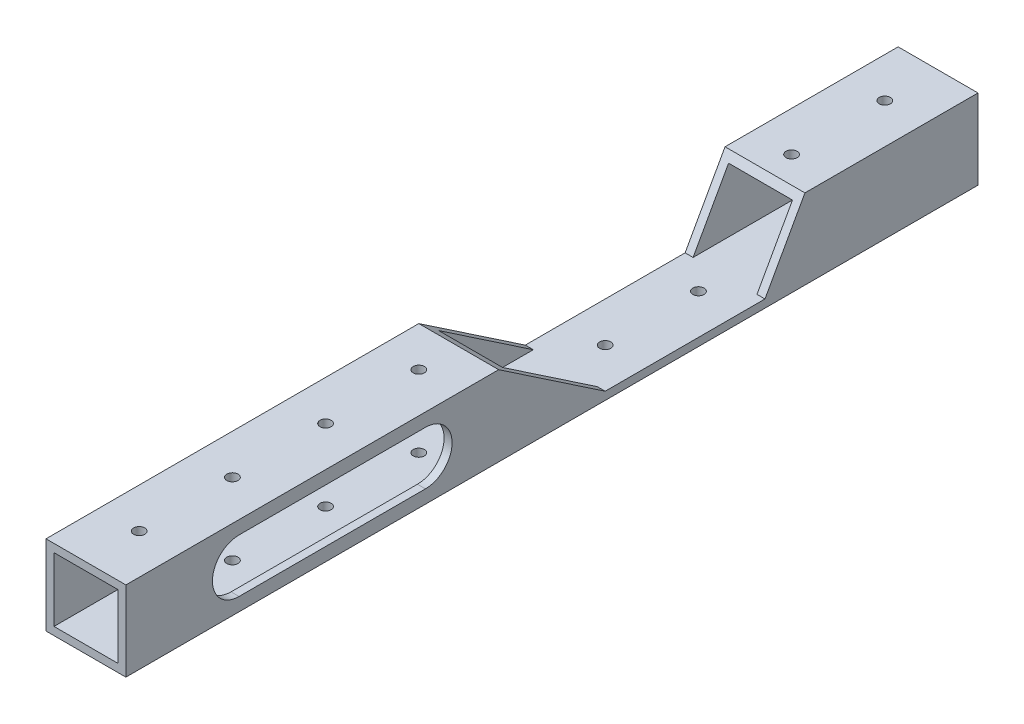
SolidWorks part; units mm, degrees
material "6061 合金"
ref_plane "前视基准面" through (0, 0, 0) normal (0, 0, 1) x (1, 0, 0)
ref_plane "上视基准面" through (0, 0, 0) normal (0, 1, 0) x (1, 0, 0)
ref_plane "右视基准面" through (0, 0, 0) normal (1, 0, 0) x (0, 0, -1)
sketch "草图1" plane through (0, 0, 0) normal (0, 0, 1) x (1, 0, 0)
  line L1 (0, 0) -> (30, 0)
  line L2 (0, 0) -> (0, 30)
  line L3 (0, 30) -> (30, 30)
  line L4 (30, 0) -> (30, 30)
  dimension "D1" = 30
  dimension "D2" = 30
extrude "拉伸-薄壁1" add sketch "草图1" along normal blind 320 thin thin type one direction reverse wall 3
sketch "草图2" plane through (30, 0, 0) normal (1, 0, 0) x (0, 0, -1)
  line L0 (-160, 30) -> (-160, 0) construction
  line L1 (-320, 30) -> (0, 30) construction
  line L2 (-320, 0) -> (0, 0) construction
  line L3 (-320, 15) -> (0, 15) construction
  line L4 (-320, 0) -> (-320, 30) construction
  line L5 (0, 0) -> (0, 30) construction
  line L6 (-242.5, 0) -> (-242.5, 30) construction
  line L7 (-277.5, 15) -> (-207.5, 15) construction
  line L8 (-277.5, 25) -> (-207.5, 25)
  line L9 (-277.5, 5) -> (-207.5, 5)
  arc A1 (-277.5, 25) -> (-277.5, 5) centre (-277.5, 15) ccw
  arc A2 (-207.5, 5) -> (-207.5, 25) centre (-207.5, 15) ccw
  point P14 (-242.5, 15)
  point P17 (-242.5, 15)
  point P20 (-242.5, 15)
  dimension "D1" = 82.5
  dimension "D2" = 30
  dimension "D3" = 20
  dimension "D4" = 70
extrude "切除-拉伸1" cut sketch "草图2" against normal through all
sketch "草图3" plane through (0, 30, 0) normal (0, 1, 0) x (1, 0, 0)
  line L0 (0, -160) -> (30, -160) construction
  line L1 (0, -320) -> (0, 0) construction
  line L2 (30, -320) -> (30, 0) construction
  line L3 (15, 0) -> (15, -320) construction
  line L4 (30, 0) -> (0, 0) construction
  line L5 (30, -320) -> (0, -320) construction
  circle A0 centre (15, -20) radius 2.1
  circle A1 centre (15, -55) radius 2.1
  circle A2 centre (15, -90) radius 2.1
  circle A3 centre (15, -125) radius 2.1
  circle A4 centre (15, -300) radius 2.1
  circle A5 centre (15, -265) radius 2.1
  circle A6 centre (15, -230) radius 2.1
  circle A7 centre (15, -195) radius 2.1
  circle A8 centre (15, -160) radius 2.1
  dimension "D1" = 20
  dimension "D2" = 35
  dimension "D3" = 35
  dimension "D4" = 35
  dimension "D5" = 35
  dimension "D6" = 160
extrude "切除-拉伸2" cut sketch "草图3" against normal through all
sketch "草图4" plane through (0, 0, 0) normal (1, 0, 0) x (0, 0, -1)
  line L0 (-160, 30) -> (-160, 0) construction
  line L1 (-320, 30) -> (0, 30) construction
  line L2 (-320, 0) -> (0, 0) construction
  line L3 (-140, 3) -> (-180, 30)
  line L4 (-180, 30) -> (-160, 30) construction
  line L5 (-180, 30) -> (0, 30)
  line L6 (-140, 3) -> (0, 3)
  line L7 (0, 3) -> (0, 30)
  line L8 (-140, 3) -> (-140, 30) construction
  line L9 (-75, 3) -> (-75, 30) construction
  line L10 (-75, 3) -> (-80, 3)
  line L11 (-80, 3) -> (-65, 30)
  dimension "D1" = 20
  dimension "D2" = 20
  dimension "D3" = 27
  dimension "D4" = 75
  dimension "D5" = 5
  dimension "D6" = 10
extrude "切除-拉伸4" cut sketch "草图4" along normal through all contours L6 L11 L5 L3
